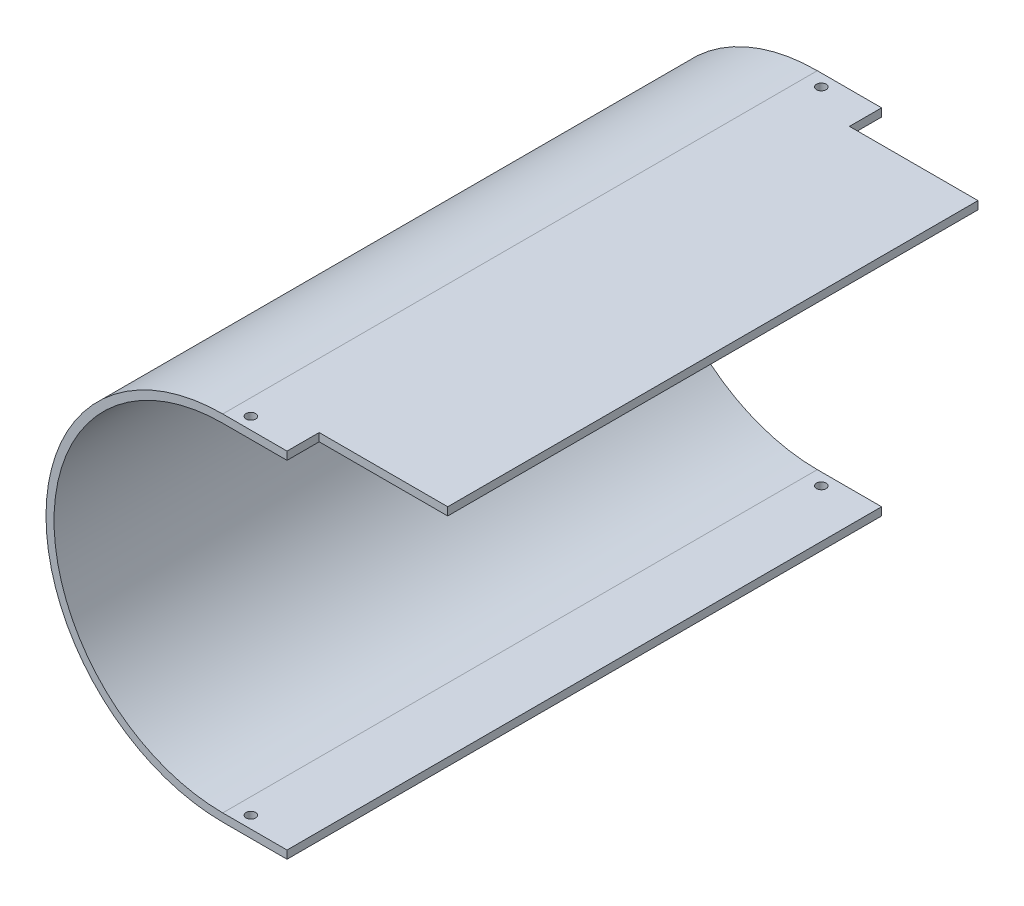
SolidWorks part; units mm, degrees
ref_plane "Front Plane" through (0, 0, 0) normal (0, 0, 1) x (1, 0, 0)
ref_plane "Top Plane" through (0, 0, 0) normal (0, 1, 0) x (1, 0, 0)
ref_plane "Right Plane" through (0, 0, 0) normal (1, 0, 0) x (0, 0, -1)
sketch "Sketch1" plane through (0, 0, 0) normal (0, 0, 1) x (1, 0, 0)
  line L0 (-60, 55) -> (0, 55)
  line L1 (0, 55) -> (0, 52.5)
  line L2 (0, -55) -> (-60, -55)
  line L3 (-60, -52.5) -> (0, -52.5)
  line L4 (-60, 52.5) -> (0, 52.5)
  line L5 (0, -52.5) -> (0, -55)
  line L6 (-40, 67.527) -> (-40, -75.565)
  arc A0 (-60, 52.5) -> (-60, -52.5) centre (-60, 0) ccw
  arc A1 (-60, 55) -> (-60, -55) centre (-60, 0) ccw
  dimension "D1" = 105
  dimension "D2" = 110
  dimension "D3" = 60
  dimension "D4" = 40
extrude "Boss-Extrude1" add sketch "Sketch1" along normal mid plane 185 contours L0 A1 L2 L6 L3 A0 L4
sketch "Sketch2" plane through (0, -55, 0) normal (0, -1, 0) x (1, 0, 0)
  line L1 (-40, 85) -> (40, 85)
  line L2 (-40, 85) -> (-40, -85)
  line L3 (-40, -85) -> (40, -85)
  line L4 (40, 85) -> (40, -85)
  line L5 (-40, 85) -> (40, -85) construction
  line L6 (-40, -85) -> (40, 85) construction
  point P0 (0, 0)
  dimension "D1" = 80
  dimension "D2" = 170
extrude "Cut-Extrude1" [suppressed] cut sketch "Sketch2" against normal up to surface (2.5 mm away)
fillet "Fillet1" [suppressed] radius 10
sketch "Sketch3" plane through (0, 0, 0) normal (0, 1, 0) x (1, 0, 0)
  line L0 (0, 88.75) -> (-55, 88.75) construction
  line L2 (-134.0249, 0) -> (85.3232, 0) construction
  line L3 (-60, 92.5) -> (-40, 92.5) construction
  circle A1 centre (-55, 88.75) radius 1.5
  circle A2 centre (-44, 88.75) radius 1.5 [skipped]
  circle A3 centre (-33, 88.75) radius 1.5
  circle A4 centre (-22, 88.75) radius 1.5 [skipped]
  circle A5 centre (-11, 88.75) radius 1.5
  circle A6 centre (0, 88.75) radius 1.5 [skipped]
  circle A7 centre (11, 88.75) radius 1.5 [skipped]
  circle A8 centre (22, 88.75) radius 1.5 [skipped]
  circle A9 centre (33, 88.75) radius 1.5 [skipped]
  circle A10 centre (44, 88.75) radius 1.5 [skipped]
  circle A11 centre (55, 88.75) radius 1.5 [skipped]
  circle A12 centre (-11, -88.75) radius 1.5
  circle A13 centre (-33, -88.75) radius 1.5
  circle A14 centre (-55, -88.75) radius 1.5
  dimension "D1" = 55
  dimension "D2" = 3
  dimension "D4" = 3.75
  dimension "D3" = 11
extrude "Cut-Extrude2" cut sketch "Sketch3" against normal through all both and the other way through all
sketch "Sketch4" plane through (0, 55, 0) normal (0, 1, 0) x (1, 0, 0)
  line L0 (-40, -92.5) -> (-40, 92.5) construction
  line L1 (40, 82.5) -> (-40, 82.5)
  line L2 (40, 82.5) -> (40, -82.5)
  line L3 (40, -82.5) -> (-40, -82.5)
  line L4 (-40, 82.5) -> (-40, -82.5)
  line L5 (40, 82.5) -> (-40, -82.5) construction
  line L6 (40, -82.5) -> (-40, 82.5) construction
  line L7 (-60, -92.5) -> (-40, -92.5) construction
  line L8 (0, 88.3444) -> (0, -88.0423)
  point P0 (0, 0)
  line M7 (-40, -92.5) -> (-40, 92.5)
  dimension "D1" = 10
extrude "Boss-Extrude2" add sketch "Sketch4" against normal up to surface (2.5 mm away) contours L8 L1 L3 M7 up to face at (-55, 52.5, 90.25)
